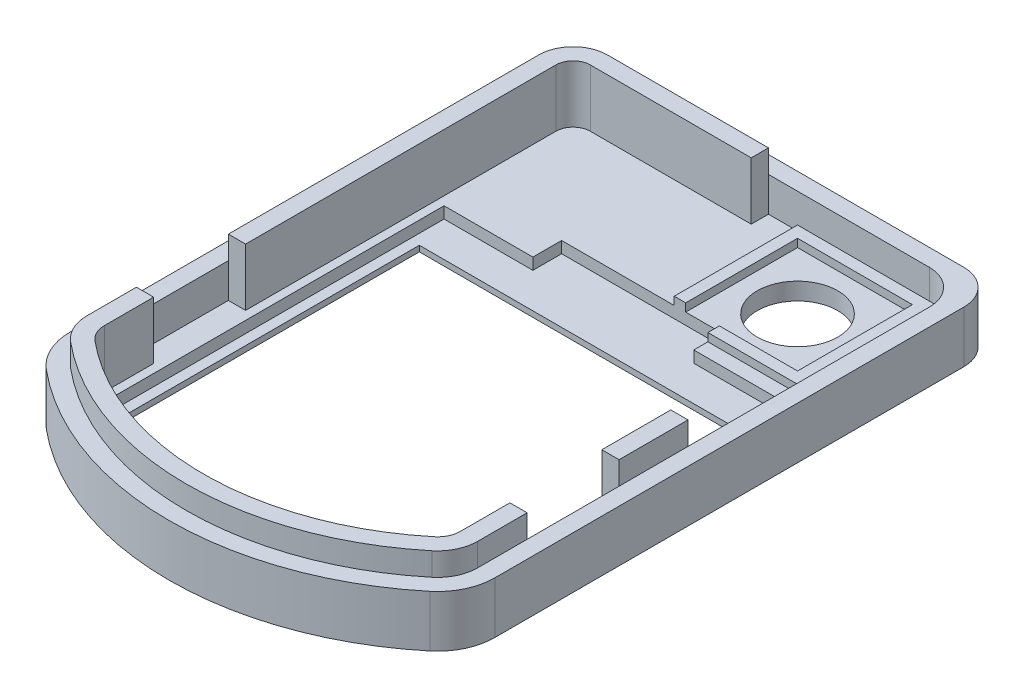
SolidWorks part; units mm, degrees
ref_plane "Front Plane" through (0, 0, 0) normal (0, 0, 1) x (1, 0, 0)
ref_plane "Top Plane" through (0, 0, 0) normal (0, 1, 0) x (1, 0, 0)
ref_plane "Right Plane" through (0, 0, 0) normal (1, 0, 0) x (0, 0, -1)
sketch "Sketch1" plane through (0, 0, 0) normal (0, 1, 0) x (1, 0, 0)
  line L0 (0, -43.7979) -> (0, -43)
  line L1 (3, 0) -> (34, 0)
  line L2 (0, -3) -> (0, -43)
  line L4 (37, -3) -> (37, -43)
  line L7 (37, -43) -> (37, -43.7979)
  arc A2 (34, 0) -> (37, -3) centre (34, -3) cw
  arc A3 (0, -3) -> (3, 0) centre (3, -3) cw
  arc A4 (35.1895, -47.6484) -> (1.8105, -47.6484) centre (18.5, -27.5) cw
  arc A5 (35.1895, -47.6484) -> (37, -43.7979) centre (32, -43.7979) ccw
  arc A6 (1.8105, -47.6484) -> (0, -43.7979) centre (5, -43.7979) cw
  circle A7 centre (27.28, -7.75) radius 3.5
  point P9 (37, -46)
  point P12 (37, 0)
  point P15 (0, 0)
  dimension "D3" = 5
  dimension "D5" = 7
  dimension "D1" = 37
  dimension "D2" = 46
  dimension "D4" = 40
  dimension "D6" = 9.72
  dimension "D7" = 7.75
extrude "Boss-Extrude1" add sketch "Sketch1" along normal blind 1.5
ref_plane "Plane1" through (0, 1.5, 0) normal (0, 1, 0) x (1, 0, 0)
sketch "Sketch2" plane through (0, 1.5, 0) normal (0, 1, 0) x (1, 0, 0)
  line L0 (0, -43.7979) -> (0, -43)
  line L1 (3, 0) -> (34, 0)
  line L2 (0, -3) -> (0, -43)
  line L4 (37, -3) -> (37, -43)
  line L9 (37, -43) -> (37, -43.7979)
  line L10 (1.5, -43.7979) -> (1.5, -43)
  line L11 (1.5, -4.5) -> (1.5, -43)
  line L12 (4.5, -1.5) -> (32.5, -1.5)
  line L13 (35.5, -4.5) -> (35.5, -43)
  line L14 (35.5, -43) -> (35.5, -43.7979)
  line L16 (3, -1.5) -> (34, -1.5) construction
  line L17 (1.5, -3) -> (1.5, -43) construction
  line L18 (35.5, -3) -> (35.5, -43) construction
  arc A0 (34, 0) -> (37, -3) centre (34, -3) cw
  arc A3 (3, 0) -> (0, -3) centre (3, -3) ccw
  arc A4 (35.5, -4.5) -> (32.5, -1.5) centre (32.5, -4.5) ccw
  arc A7 (1.5, -4.5) -> (4.5, -1.5) centre (4.5, -4.5) cw
  arc A8 (35.1895, -47.6484) -> (1.8105, -47.6484) centre (18.5, -27.5) cw
  arc A9 (1.8105, -47.6484) -> (0, -43.7979) centre (5, -43.7979) cw
  arc A10 (35.1895, -47.6484) -> (37, -43.7979) centre (32, -43.7979) ccw
  arc A14 (34.2327, -46.4933) -> (2.7673, -46.4933) centre (18.5, -27.5) cw
  arc A15 (2.7673, -46.4933) -> (1.5, -43.7979) centre (5, -43.7979) cw
  arc A18 (34.2327, -46.4933) -> (35.5, -43.7979) centre (32, -43.7979) ccw
  arc A19 (3, -1.5) -> (1.5, -3) centre (3, -3) ccw construction
  arc A20 (34, -1.5) -> (35.5, -3) centre (34, -3) cw construction
  point P7 (37, 0)
  point P12 (37, -46)
  point P15 (0, 0)
  point P22 (35.5, -1.5)
  point P25 (35.5, -44.5)
  point P30 (1.5, -1.5)
  point P38 (37, -46)
  point P40 (35.5, -43.7979)
  point P41 (32, -43.7979)
  point P42 (34.2327, -46.4933)
  point P44 (2.7673, -46.4933)
  point P45 (5, -43.7979)
  point P46 (1.5, -43.7979)
  dimension "D3" = 3
  dimension "D8" = 3
  dimension "D9" = 5
  dimension "D1" = 37
  dimension "D2" = 46
  dimension "D4" = 34
  dimension "D5" = 43
  dimension "D7" = 1.5
extrude "Boss-Extrude2" add sketch "Sketch2" along normal blind 3
sketch "Sketch3" plane through (0, 1.5, 0) normal (0, 1, 0) x (1, 0, 0)
  line L0 (32.5, -1.5) -> (4.5, -1.5) construction
  line L1 (21.28, -1.75) -> (33.28, -1.75)
  line L2 (21.28, -1.75) -> (21.28, -13.75)
  line L3 (21.28, -13.75) -> (33.28, -13.75)
  line L4 (33.28, -1.75) -> (33.28, -13.75)
  line L5 (35.5, -43.7979) -> (35.5, -4.5) construction
  line L6 (22.28, -2.75) -> (32.28, -2.75)
  line L7 (32.28, -2.75) -> (32.28, -12.75)
  line L8 (22.28, -12.75) -> (32.28, -12.75)
  line L9 (22.28, -2.75) -> (22.28, -12.75)
  dimension "D1" = 12
  dimension "D2" = 12
  dimension "D3" = 0.25
  dimension "D4" = 2.22
  dimension "D5" = 1
extrude "Boss-Extrude3" add sketch "Sketch3" along normal blind 0.7
sketch "Sketch4" plane through (0, 1.5, 0) normal (0, 1, 0) x (1, 0, 0)
  line L16 (11.48, -12.48) -> (11.48, -14.98)
  line L20 (25.48, -12.48) -> (25.48, -14.98)
  line L29 (11.48, -12.48) -> (25.48, -12.48)
  line L30 (11.48, -14.98) -> (25.48, -14.98)
  point P12 (1.48, -12.73)
  point P13 (35.52, -12.73)
  point P14 (35.5, -48.98)
  point P15 (1.5, -48.98)
  dimension "D5" = 2.5
  dimension "D6" = 2.5
sketch "Sketch5" plane through (0, 1.5, 0) normal (0, 1, 0) x (1, 0, 0)
  line L1 (4.65, -18.03) -> (32.31, -18.03)
  line L2 (4.65, -18.03) -> (4.65, -45.69)
  line L3 (4.65, -45.69) -> (32.31, -45.69)
  line L4 (32.31, -18.03) -> (32.31, -45.69)
  dimension "D1" = 27.66
  dimension "D2" = 27.66
extrude "Cut-Extrude1" cut sketch "Sketch5" against normal through all
sketch "Sketch6" plane through (0, 1.5, 0) normal (0, 1, 0) x (1, 0, 0)
  line L1 (3.75, -14.98) -> (33.25, -14.98)
  line L2 (3.75, -14.98) -> (3.75, -46.79)
  line L3 (3.75, -46.79) -> (33.25, -46.79)
  line L4 (33.25, -14.98) -> (33.25, -46.79)
  point P5 (0, 0)
  dimension "D1" = 31.81
  dimension "D2" = 29.5
extrude "Cut-Extrude2" cut sketch "Sketch6" against normal blind 1 and the other way through all
extrude "Cut-Extrude3" cut sketch "Sketch4" against normal blind 1 and the other way through all
ref_plane "Plane2" through (0, 4.5, 0) normal (0, 1, 0) x (1, 0, 0)
sketch "Sketch8" plane through (0, 4.5, 0) normal (0, 1, 0) x (1, 0, 0)
  line L0 (1.5, -4.5) -> (1.5, -31.5)
  line L1 (4.5, -1.5) -> (18.5, -1.5)
  line L2 (35.5, -25.5) -> (35.5, -31.5)
  line L3 (35.5, -43) -> (35.5, -43.7979)
  line L4 (1.5, -43) -> (1.5, -43.7979)
  line L5 (3, -43) -> (3, -43.7979)
  line L6 (34, -43) -> (34, -43.7979)
  line L7 (34, -25.5) -> (34, -31.5)
  line L8 (4.5, -3) -> (18.5, -3)
  line L9 (3, -4.5) -> (3, -31.5)
  line L10 (3, -39.5) -> (1.5, -39.5)
  line L11 (1.5, -31.5) -> (3, -31.5)
  line L12 (18.5, -1.5) -> (18.5, -52.163) construction
  line L13 (34, -39.5) -> (35.5, -39.5)
  line L14 (35.5, -31.5) -> (34, -31.5)
  line L15 (34, -25.5) -> (35.5, -25.5)
  line L16 (18.5, -1.5) -> (18.5, -3)
  line L17 (34, -39.5) -> (34, -43)
  line L18 (4.5, -1.5) -> (32.5, -1.5) construction
  line L19 (4.5, -3) -> (32.5, -3) construction
  line L20 (35.5, -4.5) -> (35.5, -43) construction
  line L21 (34, -4.5) -> (34, -43) construction
  line L22 (35.5, -39.5) -> (35.5, -43)
  line L23 (3, -39.5) -> (3, -43)
  line L24 (1.5, -39.5) -> (1.5, -43)
  line L25 (3, -4.5) -> (3, -43) construction
  line L27 (1.5, -4.5) -> (1.5, -43) construction
  arc A1 (1.5, -4.5) -> (4.5, -1.5) centre (4.5, -4.5) cw
  arc A2 (34.2327, -46.4933) -> (2.7673, -46.4933) centre (18.5, -27.5) cw
  arc A3 (2.7673, -46.4933) -> (1.5, -43.7979) centre (5, -43.7979) cw
  arc A4 (34.2327, -46.4933) -> (35.5, -43.7979) centre (32, -43.7979) ccw
  arc A5 (3.7242, -45.3381) -> (3, -43.7979) centre (5, -43.7979) cw
  arc A6 (33.2758, -45.3381) -> (3.7242, -45.3381) centre (18.5, -27.5) cw
  arc A7 (33.2758, -45.3381) -> (34, -43.7979) centre (32, -43.7979) ccw
  arc A9 (3, -4.5) -> (4.5, -3) centre (4.5, -4.5) cw
  arc A10 (34, -4.5) -> (32.5, -3) centre (32.5, -4.5) ccw construction
  arc A11 (35.5, -4.5) -> (32.5, -1.5) centre (32.5, -4.5) ccw construction
  dimension "D2" = 38
  dimension "D3" = 8
  dimension "D4" = 6
  dimension "D1" = 1.5
extrude "Boss-Extrude5" add sketch "Sketch8" along normal blind 2 and the other way up to surface
ref_plane "Plane3" through (18.5, 0, 0) normal (1, 0, 0) x (0, 0, -1)
mirror "Mirror3" [suppressed] about plane through (0, 0, 0) normal (1, 0, 0)
